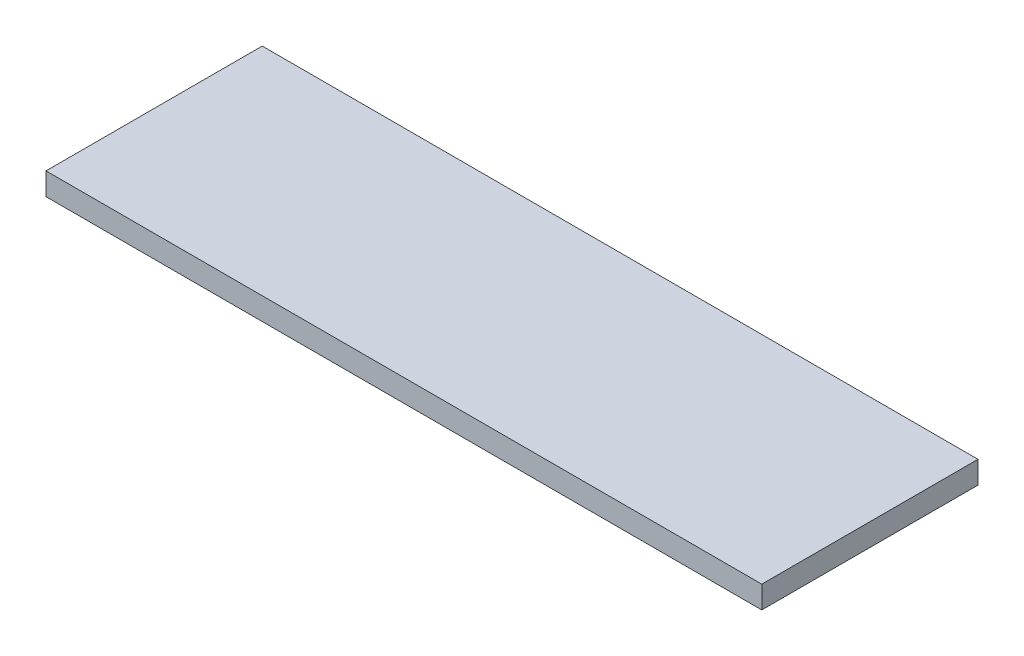
SolidWorks part; units mm, degrees
ref_plane "Front Plane" through (0, 0, 0) normal (0, 0, 1) x (1, 0, 0)
ref_plane "Top Plane" through (0, 0, 0) normal (0, 1, 0) x (1, 0, 0)
ref_plane "Right Plane" through (0, 0, 0) normal (1, 0, 0) x (0, 0, -1)
sketch "Sketch1" plane through (0, 0, 0) normal (0, 1, 0) x (1, 0, 0)
  line L1 (-304.8, 92.075) -> (304.8, 92.075)
  line L2 (-304.8, 92.075) -> (-304.8, -92.075)
  line L3 (-304.8, -92.075) -> (304.8, -92.075)
  line L4 (304.8, 92.075) -> (304.8, -92.075)
  line L5 (-304.8, 92.075) -> (304.8, -92.075) construction
  line L6 (-304.8, -92.075) -> (304.8, 92.075) construction
  point P0 (0, 0)
  dimension "D1" = 609.6
  dimension "D2" = 184.15
extrude "Boss-Extrude1" add sketch "Sketch1" along normal blind 19.05
